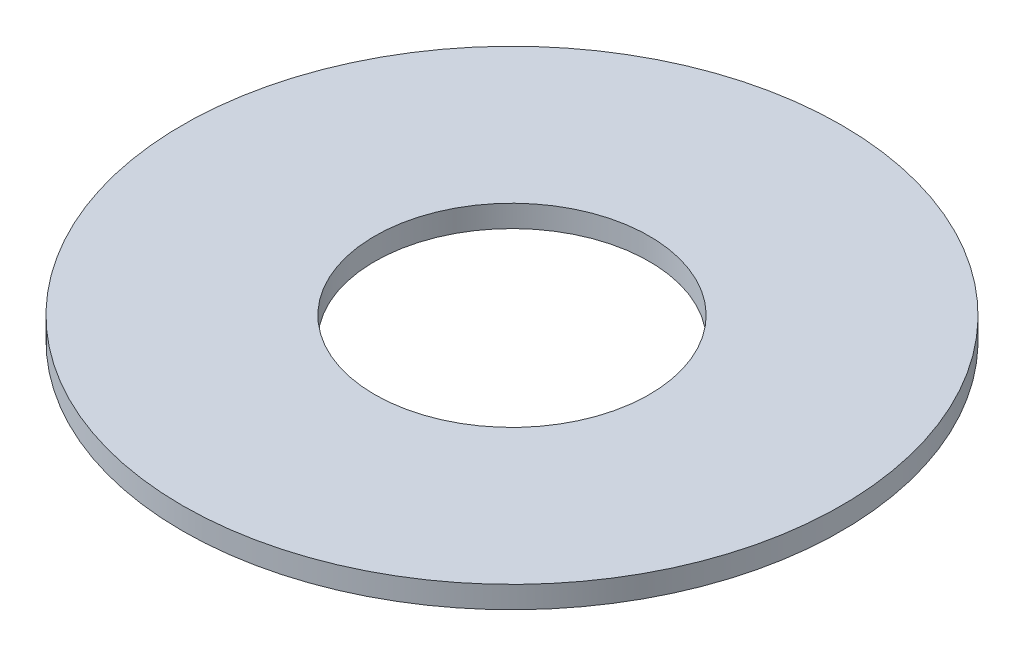
SolidWorks part; units mm, degrees
ref_plane "前视基准面" through (0, 0, 0) normal (0, 0, 1) x (1, 0, 0)
ref_plane "上视基准面" through (0, 0, 0) normal (0, 1, 0) x (1, 0, 0)
ref_plane "右视基准面" through (0, 0, 0) normal (1, 0, 0) x (0, 0, -1)
sketch "草图1" plane through (0, 0, 0) normal (0, 1, 0) x (1, 0, 0)
  circle A0 centre (0, 0) radius 15
  circle A1 centre (0, 0) radius 6.25
  dimension "D1" = 12.5
  dimension "D2" = 30
extrude "凸台-拉伸1" add sketch "草图1" along normal blind 1
